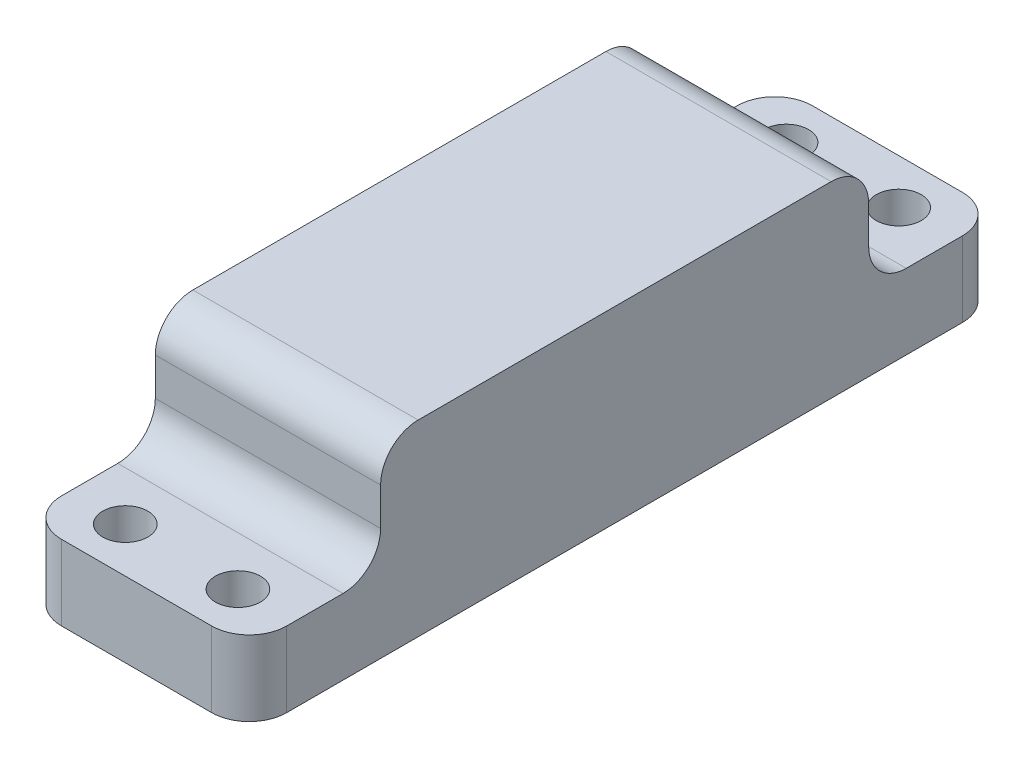
SolidWorks part; units mm, degrees
ref_plane "Front Plane" through (0, 0, 0) normal (0, 0, 1) x (1, 0, 0)
ref_plane "Top Plane" through (0, 0, 0) normal (0, 1, 0) x (1, 0, 0)
ref_plane "Right Plane" through (0, 0, 0) normal (1, 0, 0) x (0, 0, -1)
sketch "Sketch2" plane through (0, 0, 0) normal (1, 0, 0) x (0, 0, -1)
  line L0 (0, 0) -> (0, 20)
  line L1 (0, 20) -> (25, 20)
  line L2 (35, 30) -> (35, 40)
  line L3 (45, 50) -> (155, 50)
  line L4 (165, 40) -> (165, 30)
  line L5 (175, 20) -> (200, 20)
  line L6 (200, 20) -> (200, 0)
  line L7 (200, 0) -> (0, 0)
  line L8 (0, -3) -> (200, -3) construction
  arc A0 (165, 40) -> (155, 50) centre (155, 40) ccw
  arc A1 (35, 40) -> (45, 50) centre (45, 40) cw
  arc A2 (175, 20) -> (165, 30) centre (175, 30) cw
  arc A3 (35, 30) -> (25, 20) centre (25, 30) cw
  point P13 (165, 50)
  point P16 (35, 50)
  dimension "D5" = 10
  dimension "D1" = 50
  dimension "D2" = 200
  dimension "D3" = 130
  dimension "D4" = 53
  dimension "D6" = 20
extrude "Boss-Extrude1" add sketch "Sketch2" against normal blind 60
hole_wizard "CBORE for M5 Hex Head Bolt1" positions "Sketch7" profile "Sketch9" counterbore size "M5" standard "ISO" end condition through all
sketch "Sketch7" plane through (0, 20, 0) normal (0, 1, 0) x (1, 0, 0)
  line L0 (-45, 188) -> (-45, 12) construction
  line L1 (-45, 12) -> (-15, 12) construction
  line L2 (-15, 12) -> (-15, 188) construction
  line L3 (-15, 188) -> (-45, 188) construction
  line L5 (-60, 200) -> (-60, 175) construction
  line L6 (-60, 200) -> (0, 200) construction
  line L7 (-60, 0) -> (0, 0) construction
  point P0 (-15, 12)
  point P2 (-45, 12)
  point P4 (-45, 188)
  point P6 (-15, 188)
  dimension "D1" = 15
  dimension "D2" = 12
  dimension "D3" = 12
  dimension "D4" = 30
sketch "Sketch9" plane through (-15, 20, -12) normal (1, 0, 0) x (0, 0, 1)
  line L0 (0, 0) -> (0, 20)
  line L1 (0, 20) -> (4, 20)
  line L3 (4, 20) -> (4, 10)
  line L4 (4, 10) -> (6, 10)
  line L5 (6, 10) -> (6, 0)
  line L7 (6, 0) -> (0, 0)
  line L11 (0, -6.35) -> (0, 107.95) construction
  dimension "Thru Hole Dia." = 8
  dimension "Thru Hole Depth" = 20
  dimension "C'Bore Dia." = 12
  dimension "C'Bore Depth" = 10
fillet "Fillet1" radius 10 1 edges at (-60, 10, -200)
fillet "Fillet2" radius 10 1 edges at (0, 10, -200)
fillet "Fillet3" radius 10 1 edges at (0, 10, 0)
fillet "Fillet4" radius 10 1 edges at (-60, 10, 0)
